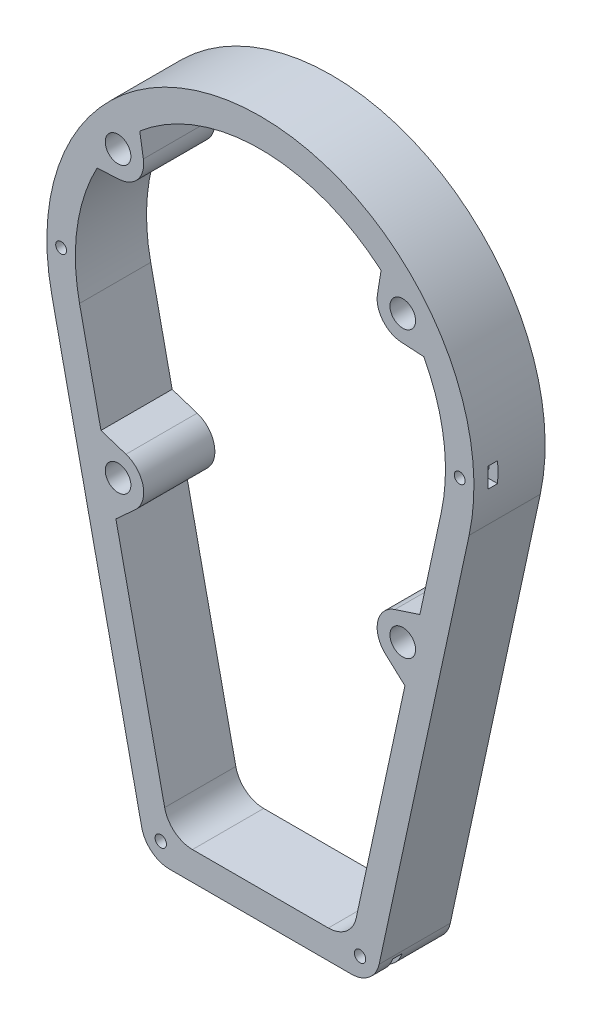
SolidWorks part; units mm, degrees
ref_plane "Front Plane" through (0, 0, 0) normal (0, 0, 1) x (1, 0, 0)
ref_plane "Top Plane" through (0, 0, 0) normal (0, 1, 0) x (1, 0, 0)
ref_plane "Right Plane" through (0, 0, 0) normal (1, 0, 0) x (0, 0, -1)
sketch "Sketch2" plane through (0, 0, 0) normal (0, 0, 1) x (1, 0, 0)
  line L0 (0, -170) -> (0, 75) construction
  line L1 (-63.5339, -13.7273) -> (-31.9299, -160)
  line L2 (-31.9299, -160) -> (31.9299, -160)
  line L3 (-40, -170) -> (40, -170)
  line L4 (40, -170) -> (73.3084, -15.8392)
  line L5 (-73.3084, -15.8392) -> (-40, -170)
  line L6 (31.9299, -160) -> (63.5339, -13.7273)
  arc A1 (73.3084, -15.8392) -> (-73.3084, -15.8392) centre (0, 0) ccw
  arc A2 (-73.3084, -15.8392) -> (0, -75) centre (0, 0) ccw construction
  arc A3 (0, -75) -> (73.3084, -15.8392) centre (0, 0) ccw construction
  arc A4 (63.5339, -13.7273) -> (-63.5339, -13.7273) centre (0, 0) ccw
  point P14 (0, -170)
  dimension "D2" = 10
  dimension "D3" = 150
  dimension "D1" = 245
  dimension "D4" = 80
extrude "Boss-Extrude1" add sketch "Sketch2" along normal blind 25
sketch "Sketch1" plane through (0, 0, 0) normal (0, 0, 1) x (1, 0, 0)
  line L0 (70, 0) -> (-70, 0) construction
  line L1 (-35, -163) -> (35, -163) construction
  line L2 (-40, -170) -> (40, -170) construction
  circle A0 centre (-70, 0) radius 1.9
  circle A1 centre (70, 0) radius 1.9
  circle A2 centre (-35, -163) radius 2
  circle A3 centre (35, -163) radius 2
  point P4 (0, 0)
  point P10 (0, -170)
  point P11 (0, -163)
  dimension "D2" = 3.8
  dimension "D3" = 4
  dimension "D1" = 140
  dimension "D4" = 7
  dimension "D5" = 70
extrude "Cut-Extrude2" cut sketch "Sketch1" along normal through all
fillet "Fillet1" radius 10 4 edges at (31.9299, -160, 12.5) (-31.9299, -160, 12.5) (-40, -170, 12.5) (40, -170, 12.5)
sketch "Sketch4" plane through (0, 0, 25) normal (0, 0, 1) x (1, 0, 0)
  line L0 (-31.9299, -170) -> (31.9299, -170) construction
  line L1 (-65.9585, 0) -> (-67.9793, 3.5)
  line L2 (-67.9793, 3.5) -> (-72.0207, 3.5)
  line L3 (-72.0207, 3.5) -> (-74.0415, 0) construction
  line L4 (-74.0415, 0) -> (-72.0207, -3.5) construction
  line L5 (-72.0207, -3.5) -> (-67.9793, -3.5)
  line L6 (-67.9793, -3.5) -> (-65.9585, 0)
  line L7 (74.0415, 0) -> (72.0207, 3.5) construction
  line L8 (72.0207, 3.5) -> (67.9793, 3.5)
  line L9 (67.9793, 3.5) -> (65.9585, 0)
  line L10 (65.9585, 0) -> (67.9793, -3.5)
  line L11 (67.9793, -3.5) -> (72.0207, -3.5)
  line L12 (72.0207, -3.5) -> (74.0415, 0) construction
  line L13 (31.6894, -160.6819) -> (31.3372, -164.708)
  line L14 (31.3372, -164.708) -> (34.6478, -167.0261)
  line L15 (34.6478, -167.0261) -> (38.3106, -165.3181) construction
  line L16 (38.3106, -165.3181) -> (38.6628, -161.292) construction
  line L17 (38.6628, -161.292) -> (35.3522, -158.9739)
  line L18 (35.3522, -158.9739) -> (31.6894, -160.6819)
  line L19 (-38.3106, -165.3181) -> (-34.6478, -167.0261) construction
  line L20 (-34.6478, -167.0261) -> (-31.3372, -164.708)
  line L21 (-31.3372, -164.708) -> (-31.6894, -160.6819)
  line L22 (-31.6894, -160.6819) -> (-35.3522, -158.9739)
  line L23 (-35.3522, -158.9739) -> (-38.6628, -161.292)
  line L24 (-38.6628, -161.292) -> (-38.3106, -165.3181) construction
  line L25 (-34.6478, -167.0261) -> (-40.1399, -170.8717)
  line L26 (-40.1399, -170.8717) -> (-44.1549, -165.1376)
  line L27 (-44.1549, -165.1376) -> (-38.6628, -161.292)
  line L28 (34.6478, -167.0261) -> (39.0926, -170.1384)
  line L29 (38.6628, -161.292) -> (43.1076, -164.4043)
  line L30 (43.1076, -164.4043) -> (39.0926, -170.1384)
  line L31 (-72.0207, -3.5) -> (-78.1819, -3.5)
  line L32 (-78.1819, -3.5) -> (-78.1819, 3.5)
  line L33 (-78.1819, 3.5) -> (-72.0207, 3.5)
  line L34 (72.0207, -3.5) -> (78.7951, -3.5)
  line L35 (78.7951, -3.5) -> (78.7951, 3.5)
  line L36 (78.7951, 3.5) -> (72.0207, 3.5)
  circle A0 centre (-70, 0) radius 3.5 construction
  circle A1 centre (70, 0) radius 3.5 construction
  circle A2 centre (35, -163) radius 3.5 construction
  circle A3 centre (-35, -163) radius 3.5 construction
  dimension "D1" = 7
  dimension "D2" = 25
  dimension "D3" = 25
extrude "Cut-Extrude6" cut sketch "Sketch4" against normal blind 3.4 from offset 5 offset against normal yes
sketch "Sketch5" plane through (0, 0, 0) normal (0, 0, 1) x (1, 0, 0)
  line L1 (-50, 40) -> (50, 40) construction
  line L2 (-50, 40) -> (-50, -60) construction
  line L3 (-50, -60) -> (50, -60) construction
  line L4 (50, 40) -> (50, -60) construction
  line L6 (-31.9299, -170) -> (31.9299, -170) construction
  circle A0 centre (50, -60) radius 4.5
  circle A1 centre (-50, -60) radius 4.5
  circle A2 centre (-50, 40) radius 4.5
  circle A3 centre (50, 40) radius 4.5
  point P4 (0, -170)
  point P8 (0, -60)
  dimension "D4" = 9
  dimension "D1" = 100
  dimension "D2" = 100
  dimension "D3" = 110
sketch "Sketch6" plane through (0, 0, 25) normal (0, 0, 1) x (1, 0, 0)
  line L0 (-50.7554, -72.8703) -> (-56.0015, -48.5896)
  line L1 (-63.5339, -13.7273) -> (-33.6342, -152.1119) construction
  line L2 (-47.2213, -51.4397) -> (-56.0015, -48.5896)
  line L3 (-43.935, -66.6495) -> (-50.7554, -72.8703)
  line L4 (-53.3784, -60.73) -> (-50, -60) construction
  line L5 (0, -60) -> (0, 40) construction
  line L6 (-50, -60) -> (50, -60) construction
  line L7 (-50, 40) -> (50, 40) construction
  line L8 (43.935, -66.6495) -> (50.7554, -72.8703)
  line L9 (50.7554, -72.8703) -> (56.0015, -48.5896)
  line L10 (47.2213, -51.4397) -> (56.0015, -48.5896)
  line L11 (-58.8884, 30.4403) -> (-42.6246, 50.77)
  line L12 (-50.7565, 40.6052) -> (-50, 40) construction
  line L13 (-41.1154, 41.4366) -> (-42.6246, 50.77)
  line L14 (-49.4513, 31.0167) -> (-58.8884, 30.4403)
  line L15 (49.4513, 31.0167) -> (58.8884, 30.4403)
  line L16 (58.8884, 30.4403) -> (42.6246, 50.77)
  line L17 (41.1154, 41.4366) -> (42.6246, 50.77)
  arc A0 (-43.935, -66.6495) -> (-47.2213, -51.4397) centre (-50, -60) ccw
  arc A2 (-49.4513, 31.0167) -> (-41.1154, 41.4366) centre (-50, 40) ccw
  arc A5 (-55.1334, -52.6075) -> (-51.6235, -68.8524) centre (-50, -60) ccw construction
  arc A6 (-51.6235, -68.8524) -> (-43.935, -66.6495) centre (-50, -60) ccw construction
  arc A7 (-47.2213, -51.4397) -> (-55.1334, -52.6075) centre (-50, -60) ccw construction
  arc A8 (43.935, -66.6495) -> (47.2213, -51.4397) centre (50, -60) cw
  arc A9 (63.5339, -13.7273) -> (-63.5339, -13.7273) centre (0, 0) ccw construction
  arc A10 (-56.3461, 33.6182) -> (-49.4513, 31.0167) centre (-50, 40) ccw construction
  arc A11 (-45.1669, 47.5922) -> (-56.3461, 33.6182) centre (-50, 40) ccw construction
  arc A12 (-41.1154, 41.4366) -> (-45.1669, 47.5922) centre (-50, 40) ccw construction
  arc A13 (49.4513, 31.0167) -> (41.1154, 41.4366) centre (50, 40) cw
  point P34 (-50.7565, 40.6052)
  point P37 (-42.6246, 50.77)
  dimension "D1" = 18
  dimension "D2" = 18
extrude "Boss-Extrude2" add sketch "Sketch6" against normal up to surface (25 mm away) up to face at (-68.1, 0, 0)
extrude "Cut-Extrude7" cut sketch "Sketch5" along normal up to surface (25 mm away) up to face at (0, -37.0315, 25)
